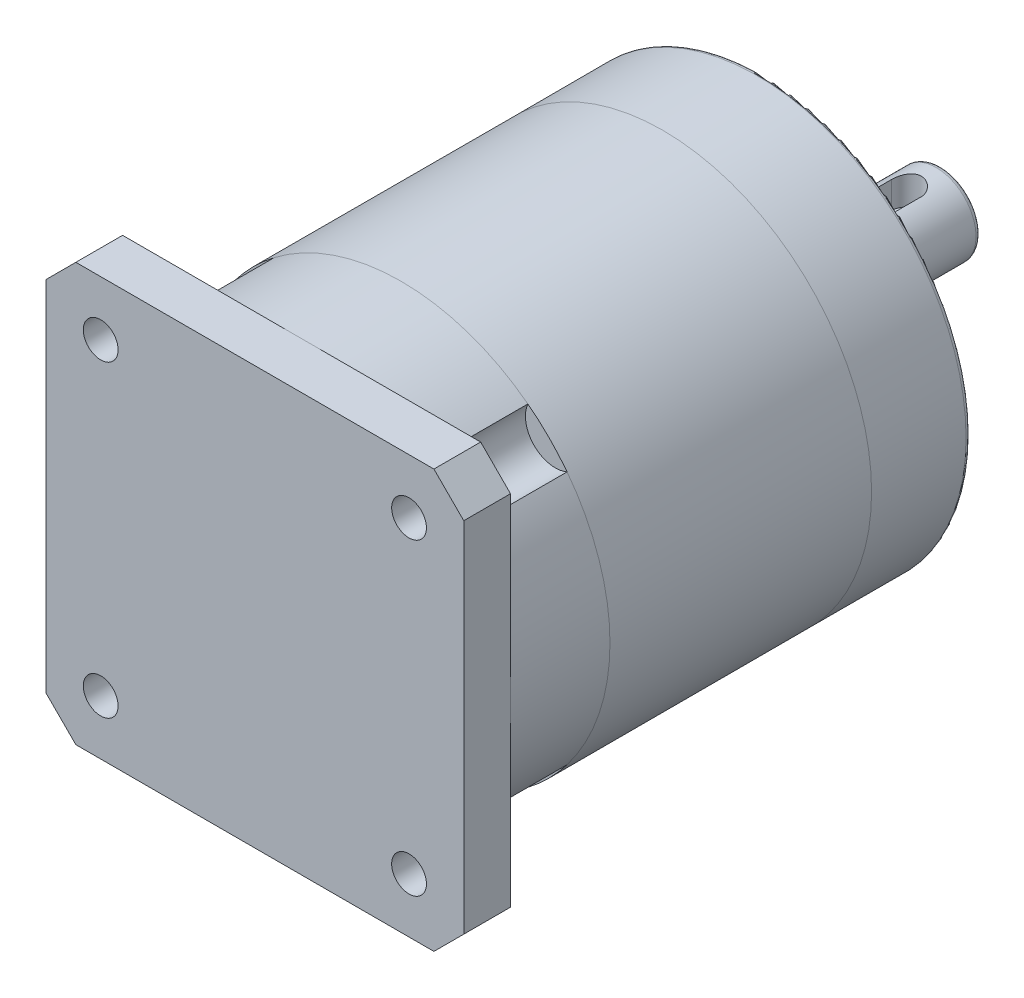
SolidWorks part; units mm, degrees
ref_plane "Front Plane" through (0, 0, 0) normal (0, 0, 1) x (1, 0, 0)
ref_plane "Top Plane" through (0, 0, 0) normal (0, 1, 0) x (1, 0, 0)
ref_plane "Right Plane" through (0, 0, 0) normal (1, 0, 0) x (0, 0, -1)
sketch "Sketch1" plane through (0, 0, 0) normal (0, 0, 1) x (1, 0, 0)
  line L0 (-21, 18) -> (-18, 21)
  line L1 (-18, 21) -> (18, 21)
  line L2 (-21, 18) -> (-21, -18)
  line L3 (-18, -21) -> (18, -21)
  line L4 (21, 18) -> (21, -18)
  line L5 (-21, 21) -> (21, -21) construction
  line L6 (-21, -21) -> (21, 21) construction
  line L7 (-21, -18) -> (-18, -21)
  line L8 (18, -21) -> (21, -18)
  line L9 (18, 21) -> (21, 18)
  point P0 (0, 0)
  dimension "D1" = 42
extrude "Boss-Extrude1" add sketch "Sketch1" along normal blind 4.7
sketch "Sketch2" plane through (0, 0, 4.7) normal (0, 0, 1) x (1, 0, 0)
  circle A0 centre (0, 0) radius 21
  dimension "D1" = 42
extrude "Boss-Extrude2" add sketch "Sketch2" against normal blind 51
sketch "Sketch3" plane through (0, 0, -46.3) normal (0, 0, -1) x (-1, 0, 0)
  circle A0 centre (0, 0) radius 4
  dimension "D1" = 8
extrude "Boss-Extrude3" add sketch "Sketch3" along normal blind 18
sketch "Sketch4" plane through (0, 0, 0) normal (0, 1, 0) x (1, 0, 0)
  line L0 (-21, 36.3) -> (21, 36.3)
  line L1 (-21, 46.3) -> (-21, 0) construction
  line L2 (21, 0) -> (21, 46.3) construction
  line L3 (21, 46.3) -> (-21, 46.3) construction
  line L4 (-21, 10) -> (21, 10)
  line L5 (18, -4.7) -> (-18, -4.7) construction
  dimension "D1" = 10
  dimension "D2" = 14.7
split line "Split Line1"
sketch "Sketch5" plane through (0, 0, 4.7) normal (0, 0, 1) x (1, 0, 0)
  line L1 (15.5, 15.5) -> (-15.5, 15.5) construction
  line L2 (15.5, 15.5) -> (15.5, -15.5) construction
  line L3 (15.5, -15.5) -> (-15.5, -15.5) construction
  line L4 (-15.5, 15.5) -> (-15.5, -15.5) construction
  line L5 (15.5, 15.5) -> (-15.5, -15.5) construction
  line L6 (15.5, -15.5) -> (-15.5, 15.5) construction
  circle A0 centre (-15.5, 15.5) radius 1.75
  circle A1 centre (15.5, 15.5) radius 1.75
  circle A2 centre (-15.5, -15.5) radius 1.75
  circle A3 centre (15.5, -15.5) radius 1.75
  point P0 (0, 0)
  dimension "D2" = 3.5
  dimension "D1" = 31
extrude "Cut-Extrude1" cut sketch "Sketch5" against normal blind 10
sketch "Sketch6" plane through (0, 0, 0) normal (0, 0, -1) x (-1, 0, 0)
  circle A0 centre (-15.5, 15.5) radius 3
  circle A1 centre (-15.5, -15.5) radius 3
  circle A2 centre (15.5, -15.5) radius 3
  circle A3 centre (15.5, 15.5) radius 3
  dimension "D1" = 6
extrude "Cut-Extrude2" cut sketch "Sketch6" along normal blind 10
ref_plane "Plane1" through (0, 4, 0) normal (0, 1, 0) x (1, 0, 0)
sketch "Sketch7" plane through (0, 4, 0) normal (0, 1, 0) x (1, 0, 0)
  line L0 (0, 60.8) -> (0, 49.8) construction
  line L1 (0, 64.3) -> (0, 46.3) construction
  line L2 (1.5, 60.8) -> (1.5, 49.8)
  line L3 (-1.5, 60.8) -> (-1.5, 49.8)
  line L4 (0, 55.3) -> (-4, 55.3) construction
  line L5 (-4, 64.3) -> (-4, 46.3) construction
  arc A0 (1.5, 60.8) -> (-1.5, 60.8) centre (0, 60.8) ccw
  arc A1 (-1.5, 49.8) -> (1.5, 49.8) centre (0, 49.8) ccw
  point P5 (0, 55.3)
  point P10 (0, 62.3)
  point P11 (0, 48.3)
  dimension "D1" = 14
  dimension "D2" = 3
extrude "Cut-Extrude3" cut sketch "Sketch7" against normal blind 3
fillet "Fillet1" radius 0.5 2 edges at (21, 0, -46.3) (-4, 0, -64.3)
sketch "Sketch8" plane through (0, 0, -46.3) normal (0, 0, -1) x (-1, 0, 0)
  circle A0 centre (0, 0) radius 17.5 construction
  circle A1 centre (0, 17.5) radius 2
  circle A2 centre (-17.5, 0) radius 2
  circle A3 centre (0, -17.5) radius 2
  circle A4 centre (17.5, 0) radius 2
  dimension "D1" = 35
  dimension "D2" = 4
extrude "Cut-Extrude4" cut sketch "Sketch8" against normal blind 10
